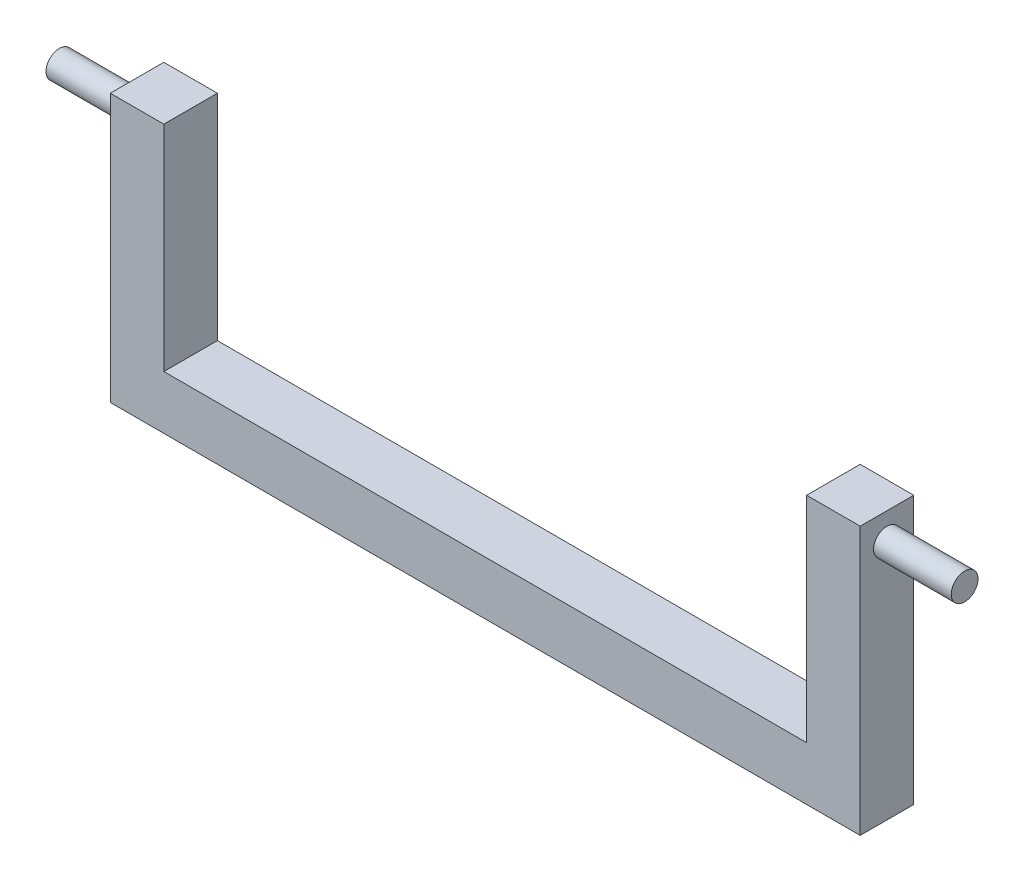
SolidWorks part; units mm, degrees
ref_plane "Front Plane" through (0, 0, 0) normal (0, 0, 1) x (1, 0, 0)
ref_plane "Top Plane" through (0, 0, 0) normal (0, 1, 0) x (1, 0, 0)
ref_plane "Right Plane" through (0, 0, 0) normal (1, 0, 0) x (0, 0, -1)
ref_plane "Plane1" through (0, 0, 190) normal (0, 0, 1) x (1, 0, 0)
sketch "Sketch1" plane through (0, 0, 190) normal (0, 0, 1) x (1, 0, 0)
  line L0 (-70, 2) -> (70, 2)
  line L1 (70, 2) -> (70, 52)
  line L2 (70, 52) -> (60, 52)
  line L3 (60, 52) -> (60, 12)
  line L4 (60, 12) -> (-60, 12)
  line L5 (-60, 12) -> (-60, 52)
  line L6 (-60, 52) -> (-70, 52)
  line L7 (-70, 52) -> (-70, 2)
extrude "Boss-Extrude1" add sketch "Sketch1" along normal mid plane 10
ref_plane "Plane2" through (-77.25, 0, 0) normal (1, 0, 0) x (0, 0, -1)
sketch "Sketch2" plane through (-77.25, 0, 0) normal (1, 0, 0) x (0, 0, -1)
  circle A0 centre (-190, 47) radius 2.5
extrude "Boss-Extrude2" add sketch "Sketch2" along normal mid plane 14.5
ref_plane "Plane3" through (77.25, 0, 0) normal (1, 0, 0) x (0, 0, -1)
sketch "Sketch3" plane through (77.25, 0, 0) normal (1, 0, 0) x (0, 0, -1)
  circle A0 centre (-190, 47) radius 2.5
extrude "Boss-Extrude3" add sketch "Sketch3" along normal mid plane 14.5
